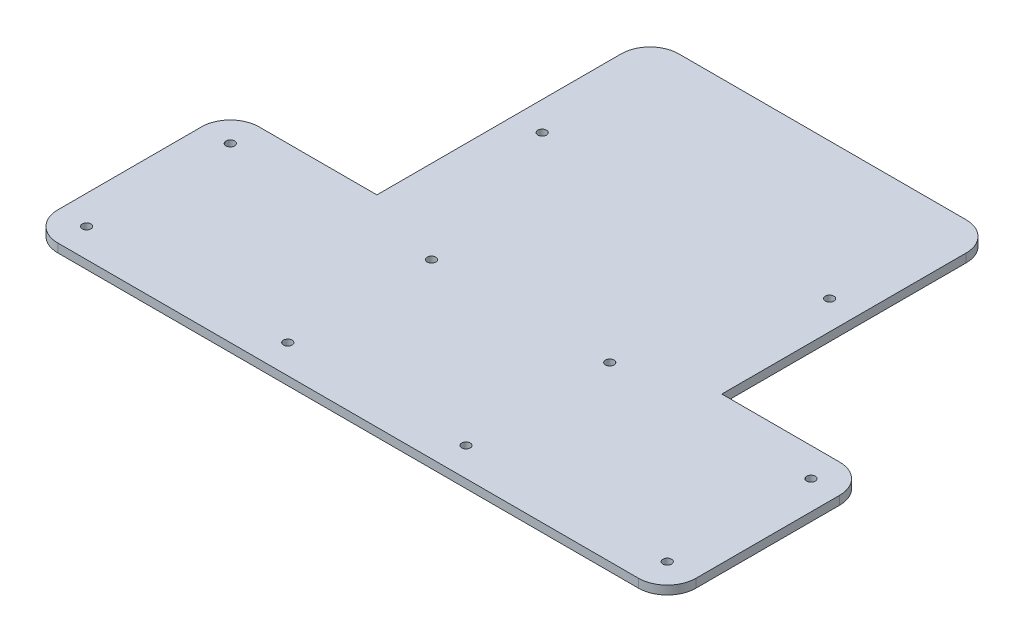
SolidWorks part; units mm, degrees
ref_plane "Front Plane" through (0, 0, 0) normal (0, 0, 1) x (1, 0, 0)
ref_plane "Top Plane" through (0, 0, 0) normal (0, 1, 0) x (1, 0, 0)
ref_plane "Right Plane" through (0, 0, 0) normal (1, 0, 0) x (0, 0, -1)
sketch "Sketch1" plane through (0, 0, 0) normal (0, 1, 0) x (1, 0, 0)
  line L0 (-60, 130) -> (60, 130)
  line L1 (60, 130) -> (60, 35)
  line L2 (60, 35) -> (111, 35)
  line L3 (111, 35) -> (111, -35)
  line L4 (111, -35) -> (-111, -35)
  line L5 (0, 130) -> (0, -35) construction
  line L6 (-111, 0) -> (111, 0) construction
  line L7 (74.5, -16.5) -> (67.5, -16.5) construction
  line L8 (96, 15) -> (71, 15) construction
  line L9 (96, 15) -> (96, -15) construction
  line L10 (96, -15) -> (71, -15) construction
  line L11 (71, 15) -> (71, -15) construction
  line L12 (83.5, -15) -> (83.5, 15) construction
  line L13 (96, 0) -> (71, 0) construction
  line L14 (74.5, 13.5) -> (67.5, 13.5) construction
  line L15 (74.5, 13.5) -> (74.5, 16.5) construction
  line L16 (74.5, 16.5) -> (67.5, 16.5) construction
  line L17 (67.5, 13.5) -> (67.5, 16.5) construction
  line L18 (71, 16.5) -> (71, 13.5) construction
  line L19 (74.5, 15) -> (67.5, 15) construction
  line L20 (74.5, -13.5) -> (67.5, -13.5) construction
  line L21 (92.5, 15) -> (99.5, 15) construction
  line L22 (96, 16.5) -> (96, 13.5) construction
  line L23 (99.5, 13.5) -> (99.5, 16.5) construction
  line L24 (92.5, 13.5) -> (92.5, 16.5) construction
  line L25 (92.5, 16.5) -> (99.5, 16.5) construction
  line L26 (92.5, 13.5) -> (99.5, 13.5) construction
  line L27 (92.5, -13.5) -> (99.5, -13.5) construction
  line L28 (92.5, -16.5) -> (99.5, -16.5) construction
  line L29 (-92.5, 13.5) -> (-92.5, 16.5) construction
  line L30 (-99.5, 13.5) -> (-99.5, 16.5) construction
  line L31 (-96, 16.5) -> (-96, 13.5) construction
  line L32 (-92.5, 15) -> (-99.5, 15) construction
  line L33 (-74.5, 15) -> (-67.5, 15) construction
  line L34 (-71, 16.5) -> (-71, 13.5) construction
  line L35 (-67.5, 13.5) -> (-67.5, 16.5) construction
  line L36 (-74.5, 13.5) -> (-74.5, 16.5) construction
  line L37 (-96, 0) -> (-71, 0) construction
  line L38 (-83.5, -15) -> (-83.5, 15) construction
  line L39 (-71, 15) -> (-71, -15) construction
  line L40 (-96, -15) -> (-71, -15) construction
  line L41 (-96, 15) -> (-96, -15) construction
  line L42 (-96, 15) -> (-71, 15) construction
  line L43 (-92.5, -16.5) -> (-99.5, -16.5) construction
  line L44 (-92.5, -13.5) -> (-99.5, -13.5) construction
  line L45 (-92.5, 13.5) -> (-99.5, 13.5) construction
  line L46 (-92.5, 16.5) -> (-99.5, 16.5) construction
  line L47 (-74.5, -13.5) -> (-67.5, -13.5) construction
  line L48 (-74.5, 16.5) -> (-67.5, 16.5) construction
  line L49 (-74.5, 13.5) -> (-67.5, 13.5) construction
  line L50 (-74.5, -16.5) -> (-67.5, -16.5) construction
  line L51 (-111, 35) -> (-111, -35)
  line L52 (-60, 35) -> (-111, 35)
  line L53 (-60, 130) -> (-60, 35)
  line L55 (-27.5, 110) -> (27.5, 110) construction
  line L56 (-27.5, 110) -> (-27.5, 55) construction
  line L57 (-27.5, 55) -> (27.5, 55) construction
  line L58 (27.5, 110) -> (27.5, 55) construction
  line L59 (0, 55) -> (0, 110) construction
  line L60 (-27.5, 82.5) -> (27.5, 82.5) construction
  line L61 (-38, 46.5) -> (38, 46.5) construction
  line L62 (-38, 46.5) -> (-38, 118.5) construction
  line L63 (-38, 118.5) -> (38, 118.5) construction
  line L64 (38, 46.5) -> (38, 118.5) construction
  line L65 (0, 118.5) -> (0, 46.5) construction
  line L66 (-38, 82.5) -> (38, 82.5) construction
  line L67 (15, -23.5) -> (-15, -23.5) construction
  line L68 (15, -23.5) -> (15, 6.5) construction
  line L69 (15, 6.5) -> (-15, 6.5) construction
  line L70 (-15, -23.5) -> (-15, 6.5) construction
  line L71 (0, 6.5) -> (0, -23.5) construction
  line L72 (15, -8.5) -> (-15, -8.5) construction
  arc A1 (74.5, 16.5) -> (74.5, 13.5) centre (74.5, 15) cw construction
  arc A2 (67.5, 16.5) -> (67.5, 13.5) centre (67.5, 15) ccw construction
  arc A3 (67.5, -16.5) -> (67.5, -13.5) centre (67.5, -15) cw construction
  arc A4 (74.5, -16.5) -> (74.5, -13.5) centre (74.5, -15) ccw construction
  arc A5 (99.5, 16.5) -> (99.5, 13.5) centre (99.5, 15) cw construction
  arc A6 (92.5, 16.5) -> (92.5, 13.5) centre (92.5, 15) ccw construction
  arc A7 (92.5, -16.5) -> (92.5, -13.5) centre (92.5, -15) cw construction
  arc A8 (99.5, -16.5) -> (99.5, -13.5) centre (99.5, -15) ccw construction
  arc A9 (-99.5, -16.5) -> (-99.5, -13.5) centre (-99.5, -15) cw construction
  arc A10 (-92.5, -16.5) -> (-92.5, -13.5) centre (-92.5, -15) ccw construction
  arc A11 (-92.5, 16.5) -> (-92.5, 13.5) centre (-92.5, 15) cw construction
  arc A12 (-99.5, 16.5) -> (-99.5, 13.5) centre (-99.5, 15) ccw construction
  arc A13 (-74.5, -16.5) -> (-74.5, -13.5) centre (-74.5, -15) cw construction
  arc A14 (-67.5, -16.5) -> (-67.5, -13.5) centre (-67.5, -15) ccw construction
  arc A15 (-67.5, 16.5) -> (-67.5, 13.5) centre (-67.5, 15) cw construction
  arc A16 (-74.5, 16.5) -> (-74.5, 13.5) centre (-74.5, 15) ccw construction
  circle A17 centre (38, 118.5) radius 1.5 construction
  circle A18 centre (38, 46.5) radius 1.5 construction
  circle A19 centre (-38, 118.5) radius 1.5 construction
  circle A20 centre (-38, 46.5) radius 1.5 construction
  circle A21 centre (-15, 6.5) radius 1.5 construction
  circle A22 centre (15, 6.5) radius 1.5 construction
  circle A23 centre (15, -23.5) radius 1.5 construction
  circle A24 centre (-15, -23.5) radius 1.5 construction
  circle A25 centre (-50, 82.5) radius 1.5
  circle A26 centre (-101, 25) radius 1.5
  circle A27 centre (-101, -25) radius 1.5
  circle A28 centre (-31, 25) radius 1.5
  circle A29 centre (-31, -25) radius 1.5
  circle A30 centre (101, 25) radius 1.5
  circle A31 centre (101, -25) radius 1.5
  circle A32 centre (31, -25) radius 1.5
  circle A33 centre (31, 25) radius 1.5
  circle A34 centre (50, 82.5) radius 1.5
  point P9 (83.5, 0)
  point P66 (0, 0)
  point P82 (-83.5, 0)
  point P83 (0, 82.5)
  point P91 (0, 82.5)
  point P92 (0, -8.5)
  dimension "D6" = 7
  dimension "D9" = 3
  dimension "D11" = 3
  dimension "D19" = 3
  dimension "D20" = 3
  dimension "D1" = 25
  dimension "D2" = 30
  dimension "D3" = 71
  dimension "D4" = 15
  dimension "D5" = 20
  dimension "D7" = 3
  dimension "D8" = 76
  dimension "D10" = 30
  dimension "D12" = 55
  dimension "D13" = 55
  dimension "D14" = 8.5
  dimension "D15" = 55
  dimension "D16" = 40
  dimension "D17" = 20
  dimension "D18" = 120
  dimension "D21" = 10
  dimension "D22" = 10
  dimension "D23" = 10
  dimension "D24" = 80
extrude "Boss-Extrude1" add sketch "Sketch1" along normal blind 3
fillet "Fillet1" radius 10 6 edges at (-60, 1.5, -130) (60, 1.5, -130) (111, 1.5, -35) (111, 1.5, 35) (-111, 1.5, 35) (-111, 1.5, -35)
